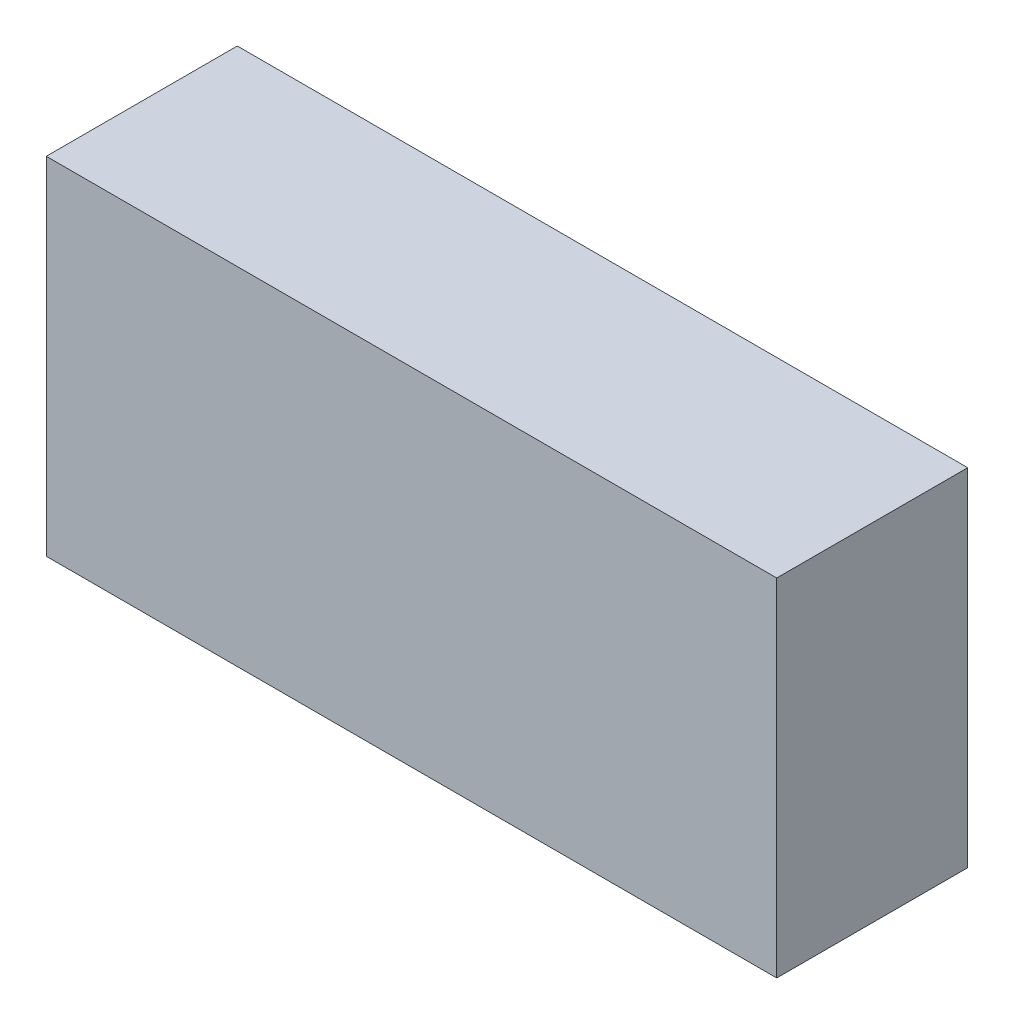
SolidWorks part; units mm, degrees
material "Custom Plastic"
ref_plane "X-Y Datum" through (0, 0, 0) normal (0, 0, 1) x (1, 0, 0)
ref_plane "X-Z Datum" through (0, 0, 0) normal (0, 1, 0) x (1, 0, 0)
ref_plane "Y-Z Datum" through (0, 0, 0) normal (1, 0, 0) x (0, 0, -1)
sketch "Sketch1" plane through (0, 0, 0) normal (0, 0, 1) x (1, 0, 0)
  line L5 (86.8736, 38.2587) -> (-70.3716, 38.2587) construction
  line L6 (-113.9708, 38.2587) -> (-113.9708, -38.2588) construction
  line L11 (-116.5108, 39.9097) -> (105.7392, 39.9097)
  line L12 (-116.5108, 39.9097) -> (-116.5108, -65.5003)
  line L13 (-116.5108, -65.5003) -> (105.7392, -65.5003)
  line L14 (105.7392, 39.9097) -> (105.7392, -65.5003)
  point P4 (0, 0)
  point P5 (0, 24.5745)
  dimension "D1" = 105.41
  dimension "D2" = 222.25
  dimension "D3" = 1.651
  dimension "D4" = 2.54
extrude "Boss-Extrude1" add sketch "Sketch1" along normal blind 27.7876 and the other way blind 30.3276
sketch "face w/o cavities 2" plane through (0, 0, 27.7876) normal (0, 0, 1) x (1, 0, 0)
  line L1018 (86.8736, 38.2587) -> (-70.3716, 38.2587) construction
  line L1019 (-70.3716, 38.2587) -> (-78.273, 38.2587) construction
  line L1027 (-78.273, 38.2587) -> (-109.9112, 38.2587) construction
  line L1028 (-109.9112, 38.2587) -> (-114.2858, 38.2587) construction
  line L1029 (-114.2858, 38.2587) -> (-114.2858, -38.2588) construction
  line L1030 (-114.2858, -38.2588) -> (-109.9112, -38.2588) construction
  line L1031 (-109.9112, -38.2588) -> (-78.273, -38.2588) construction
  line L1032 (-78.273, -38.2588) -> (-73.8188, -38.2588) construction
  line L1033 (-54.9139, -62.0546) -> (-68.4937, -41.1496) construction
  line L1034 (-45.616, -63.5) -> (-52.2514, -63.5) construction
  line L1035 (-24.1235, -40.4425) -> (-43.2199, -62.4081) construction
  line L1036 (-19.3313, -38.2588) -> (-17.4625, -38.2588) construction
  line L1037 (-11.1125, -53.6575) -> (-11.1125, -44.6088) construction
  line L1038 (4.7625, -60.0075) -> (-4.7625, -60.0075) construction
  line L1221 (11.1125, -44.6088) -> (11.1125, -53.6575) construction
  line L1222 (17.4625, -38.2588) -> (27.6548, -38.2588) construction
  line L1223 (42.3353, -61.6347) -> (33.4393, -41.9893) construction
  line L1224 (54.568, -63.5) -> (45.2276, -63.5) construction
  line L1225 (61.9212, -40.5878) -> (57.6764, -60.9723) construction
  line L1226 (94.9835, -32.6528) -> (67.4688, -35.5677) construction
  line L1227 (103.505, 25.5668) -> (103.505, -23.1808) construction
  line L1228 (90.7509, 37.4339) -> (97.8572, 34.2669) construction
  line L1229 (86.8736, 38.2587) -> (-70.3716, 38.2587) construction
  line L1230 (-70.3716, 38.2587) -> (-78.273, 38.2587) construction
  line L1231 (-78.273, 38.2587) -> (-109.9112, 38.2587) construction
  line L1232 (-109.9112, 38.2587) -> (-114.2858, 38.2587) construction
  line L1233 (-114.2858, 38.2587) -> (-114.2858, -38.2588) construction
  line L1234 (-114.2858, -38.2588) -> (-109.9112, -38.2588) construction
  line L1235 (-109.9112, -38.2588) -> (-78.273, -38.2588) construction
  line L1236 (-78.273, -38.2588) -> (-73.8188, -38.2588) construction
  line L1237 (-54.9139, -62.0546) -> (-68.4937, -41.1496) construction
  line L1238 (-45.616, -63.5) -> (-52.2514, -63.5) construction
  line L1239 (-24.1235, -40.4425) -> (-43.2199, -62.4081) construction
  line L1240 (-19.3313, -38.2588) -> (-17.4625, -38.2588) construction
  line L1241 (-11.1125, -53.6575) -> (-11.1125, -44.6088) construction
  line L1242 (4.7625, -60.0075) -> (-4.7625, -60.0075) construction
  line L1243 (11.1125, -44.6088) -> (11.1125, -53.6575) construction
  line L1244 (17.4625, -38.2588) -> (27.6548, -38.2588) construction
  line L1245 (42.3353, -61.6347) -> (33.4393, -41.9893) construction
  line L1246 (54.568, -63.5) -> (45.2276, -63.5) construction
  line L1247 (61.9212, -40.5878) -> (57.6764, -60.9723) construction
  line L1248 (94.9835, -32.6528) -> (67.4688, -35.5677) construction
  line L1249 (103.505, 25.5668) -> (103.505, -23.1808) construction
  line L1250 (90.7509, 37.4339) -> (97.8572, 34.2669) construction
  line L1251 (86.8736, 40.7987) -> (-70.3716, 40.7987)
  line L1252 (-70.3716, 40.7987) -> (-78.273, 40.7987)
  line L1253 (-78.273, 40.7987) -> (-109.9112, 40.7987)
  line L1254 (-109.9112, 40.7987) -> (-116.8258, 40.7987)
  line L1255 (-116.8258, 40.7987) -> (-116.8258, -40.7988)
  line L1256 (-116.8258, -40.7988) -> (-109.9112, -40.7988)
  line L1257 (-109.9112, -40.7988) -> (-78.273, -40.7988)
  line L1258 (-78.273, -40.7988) -> (-73.8188, -40.7988)
  line L1259 (-57.044, -63.4382) -> (-70.6238, -42.5333)
  line L1260 (-45.616, -66.04) -> (-52.2514, -66.04)
  line L1261 (-22.2067, -42.109) -> (-41.303, -64.0746)
  line L1262 (-19.3313, -40.7988) -> (-17.4625, -40.7988)
  line L1263 (-13.6525, -53.6575) -> (-13.6525, -44.6088)
  line L1264 (4.7625, -62.5475) -> (-4.7625, -62.5475)
  line L1265 (13.6525, -44.6088) -> (13.6525, -53.6575)
  line L1266 (17.4625, -40.7988) -> (27.6548, -40.7988)
  line L1267 (40.0215, -62.6825) -> (31.1255, -43.0371)
  line L1268 (54.568, -66.04) -> (45.2276, -66.04)
  line L1269 (64.4078, -41.1056) -> (60.163, -61.4901)
  line L1270 (95.2511, -35.1786) -> (67.7364, -38.0936)
  line L1271 (106.045, 25.5668) -> (106.045, -23.1808)
  line L1272 (91.7848, 39.7539) -> (98.8912, 36.587)
  arc A652 (90.7509, 37.4339) -> (86.8736, 38.2587) centre (86.8736, 28.7337) ccw construction
  arc A653 (-70.3716, -39.2759) -> (-73.8188, -38.2588) centre (-73.8188, -44.6088) ccw construction
  arc A654 (-68.4937, -41.1496) -> (-70.3716, -39.2759) centre (-73.8188, -44.6088) ccw construction
  arc A655 (-54.9139, -62.0546) -> (-52.2514, -63.5) centre (-52.2514, -60.325) ccw construction
  arc A656 (-45.616, -63.5) -> (-43.2199, -62.4081) centre (-45.616, -60.325) ccw construction
  arc A657 (-19.3313, -38.2588) -> (-24.1235, -40.4425) centre (-19.3313, -44.6088) ccw construction
  arc A658 (-11.1125, -44.6088) -> (-17.4625, -38.2588) centre (-17.4625, -44.6088) ccw construction
  arc A659 (-11.1125, -53.6575) -> (-4.7625, -60.0075) centre (-4.7625, -53.6575) ccw construction
  arc A660 (4.7625, -60.0075) -> (11.1125, -53.6575) centre (4.7625, -53.6575) ccw construction
  arc A661 (17.4625, -38.2588) -> (11.1125, -44.6088) centre (17.4625, -44.6088) ccw construction
  arc A662 (33.4393, -41.9893) -> (27.6548, -38.2588) centre (27.6548, -44.6088) ccw construction
  arc A663 (42.3353, -61.6347) -> (45.2276, -63.5) centre (45.2276, -60.325) ccw construction
  arc A664 (54.568, -63.5) -> (57.6764, -60.9723) centre (54.568, -60.325) ccw construction
  arc A665 (67.4688, -35.5677) -> (61.9212, -40.5878) centre (68.1378, -41.8824) ccw construction
  arc A666 (94.9835, -32.6528) -> (103.505, -23.1808) centre (93.98, -23.1808) ccw construction
  arc A667 (103.505, 25.5668) -> (97.8572, 34.2669) centre (93.98, 25.5668) ccw construction
  arc A668 (90.7509, 37.4339) -> (86.8736, 38.2587) centre (86.8736, 28.7337) ccw construction
  arc A669 (-70.3716, -39.2759) -> (-73.8188, -38.2588) centre (-73.8188, -44.6088) ccw construction
  arc A670 (-68.4937, -41.1496) -> (-70.3716, -39.2759) centre (-73.8188, -44.6088) ccw construction
  arc A671 (-54.9139, -62.0546) -> (-52.2514, -63.5) centre (-52.2514, -60.325) ccw construction
  arc A672 (-45.616, -63.5) -> (-43.2199, -62.4081) centre (-45.616, -60.325) ccw construction
  arc A673 (-19.3313, -38.2588) -> (-24.1235, -40.4425) centre (-19.3313, -44.6088) ccw construction
  arc A674 (-11.1125, -44.6088) -> (-17.4625, -38.2588) centre (-17.4625, -44.6088) ccw construction
  arc A675 (-11.1125, -53.6575) -> (-4.7625, -60.0075) centre (-4.7625, -53.6575) ccw construction
  arc A676 (4.7625, -60.0075) -> (11.1125, -53.6575) centre (4.7625, -53.6575) ccw construction
  arc A677 (17.4625, -38.2588) -> (11.1125, -44.6088) centre (17.4625, -44.6088) ccw construction
  arc A678 (33.4393, -41.9893) -> (27.6548, -38.2588) centre (27.6548, -44.6088) ccw construction
  arc A679 (42.3353, -61.6347) -> (45.2276, -63.5) centre (45.2276, -60.325) ccw construction
  arc A680 (54.568, -63.5) -> (57.6764, -60.9723) centre (54.568, -60.325) ccw construction
  arc A681 (67.4688, -35.5677) -> (61.9212, -40.5878) centre (68.1378, -41.8824) ccw construction
  arc A682 (94.9835, -32.6528) -> (103.505, -23.1808) centre (93.98, -23.1808) ccw construction
  arc A683 (103.505, 25.5668) -> (97.8572, 34.2669) centre (93.98, 25.5668) ccw construction
  arc A684 (-71.7505, -41.409) -> (-73.8188, -40.7988) centre (-73.8188, -44.6088) ccw
  arc A685 (-70.6238, -42.5333) -> (-71.7505, -41.409) centre (-73.8188, -44.6088) ccw
  arc A686 (-57.044, -63.4382) -> (-52.2514, -66.04) centre (-52.2514, -60.325) ccw
  arc A687 (-45.616, -66.04) -> (-41.303, -64.0746) centre (-45.616, -60.325) ccw
  arc A688 (-19.3313, -40.7988) -> (-22.2067, -42.109) centre (-19.3313, -44.6088) ccw
  arc A689 (-13.6525, -44.6088) -> (-17.4625, -40.7988) centre (-17.4625, -44.6088) ccw
  arc A690 (-13.6525, -53.6575) -> (-4.7625, -62.5475) centre (-4.7625, -53.6575) ccw
  arc A691 (4.7625, -62.5475) -> (13.6525, -53.6575) centre (4.7625, -53.6575) ccw
  arc A692 (17.4625, -40.7988) -> (13.6525, -44.6088) centre (17.4625, -44.6088) ccw
  arc A693 (31.1255, -43.0371) -> (27.6548, -40.7988) centre (27.6548, -44.6088) ccw
  arc A694 (40.0215, -62.6825) -> (45.2276, -66.04) centre (45.2276, -60.325) ccw
  arc A695 (54.568, -66.04) -> (60.163, -61.4901) centre (54.568, -60.325) ccw
  arc A696 (67.7364, -38.0936) -> (64.4078, -41.1056) centre (68.1378, -41.8824) ccw
  arc A697 (95.2511, -35.1786) -> (106.045, -23.1808) centre (93.98, -23.1808) ccw
  arc A698 (106.045, 25.5668) -> (98.8912, 36.587) centre (93.98, 25.5668) ccw
  arc A699 (91.7848, 39.7539) -> (86.8736, 40.7987) centre (86.8736, 28.7337) ccw
  dimension "D1" = 2.54
sketch "Side Stock Boundary" plane through (0, 39.9097, 0) normal (0, 1, 0) x (1, 0, 0)
  line L5 (-45.616, 28.7655) -> (-52.2514, 28.7655) construction
  line L6 (-49.3097, -7.6977) -> (-114.5398, -7.6977)
  line L7 (-49.3097, -7.6977) -> (-49.3097, 28.7655)
  line L8 (-49.3097, 28.7655) -> (-114.5398, 28.7655)
  line L9 (-114.5398, -7.6977) -> (-114.5398, 28.7655)
  arc A0 (-109.9112, 17.1495) -> (-113.9708, 9.1392) centre (-107.9358, 11.1146) ccw construction
  dimension "D1" = 6.604
  dimension "D2" = 1.27
ref_plane "Plane1" through (0, 0, 29.1106) normal (0, 0, 1) x (1, 0, 0)
sketch "faced stock boundary" [suppressed] plane through (0, 0, 25.8394) normal (0, 0, 1) x (1, 0, 0)
  line L0 (112.7242, 42.0687) -> (-119.0508, 42.0687) construction
  line L1 (103.505, 42.0687) -> (-114.2858, 42.0687)
  line L2 (103.505, 42.0687) -> (103.505, -66.3893)
  line L3 (103.505, -66.3893) -> (-114.2858, -66.3893)
  line L4 (-114.2858, 42.0687) -> (-114.2858, -66.3893)
  line L5 (-119.0508, -66.3893) -> (112.7242, -66.3893) construction
  line L6 (103.505, -23.1808) -> (103.505, 25.5668) construction
  line L7 (-114.2858, -38.2588) -> (-114.2858, 38.2587) construction
sketch "Sketch2" plane through (0, 39.9097, 0) normal (0, 1, 0) x (1, 0, 0)
  line L0 (-45.616, 28.7655) -> (-52.2514, 28.7655) construction
  line L1 (-52.9863, -4.7204) -> (-114.2858, -4.7204)
  line L2 (-52.9863, -4.7204) -> (-52.9863, 28.7655)
  line L3 (-52.9863, 28.7655) -> (-70.3716, 28.7655)
  line L4 (-114.2858, -4.7204) -> (-114.2858, 11.1146)
  line L5 (-109.9112, 17.1495) -> (-78.273, 27.5053) construction
  line L6 (-109.9112, 17.1495) -> (-78.273, 27.5053)
  arc A0 (-109.9112, 17.1495) -> (-113.9708, 9.1392) centre (-107.9358, 11.1146) ccw construction
  arc A1 (-109.9112, 17.1495) -> (-114.2858, 11.1146) centre (-107.9358, 11.1146) ccw
  arc A2 (-73.8188, 28.5305) -> (-78.273, 27.5053) centre (-70.3716, 3.3655) ccw construction
  arc A3 (-70.3716, 28.7655) -> (-73.8188, 28.5305) centre (-70.3716, 3.3655) ccw construction
  arc A4 (-73.8188, 28.5305) -> (-78.273, 27.5053) centre (-70.3716, 3.3655) ccw
  arc A5 (-70.3716, 28.7655) -> (-73.8188, 28.5305) centre (-70.3716, 3.3655) ccw
equation "\"StockLength\"= 8.750in"
equation "\"StockWidth\"= 4.150in"
equation "\"StockHeight\"= 2.288in"
equation "\"D1@Boss-Extrude1\"=(\"StockHeight\"/2)-0.05"
equation "\"D2@Boss-Extrude1\"=(\"StockHeight\"/2)+0.05"
equation "\"D2@Sketch1\"= \"StockLength\""
equation "\"D1@Sketch1\"= \"StockWidth\""
